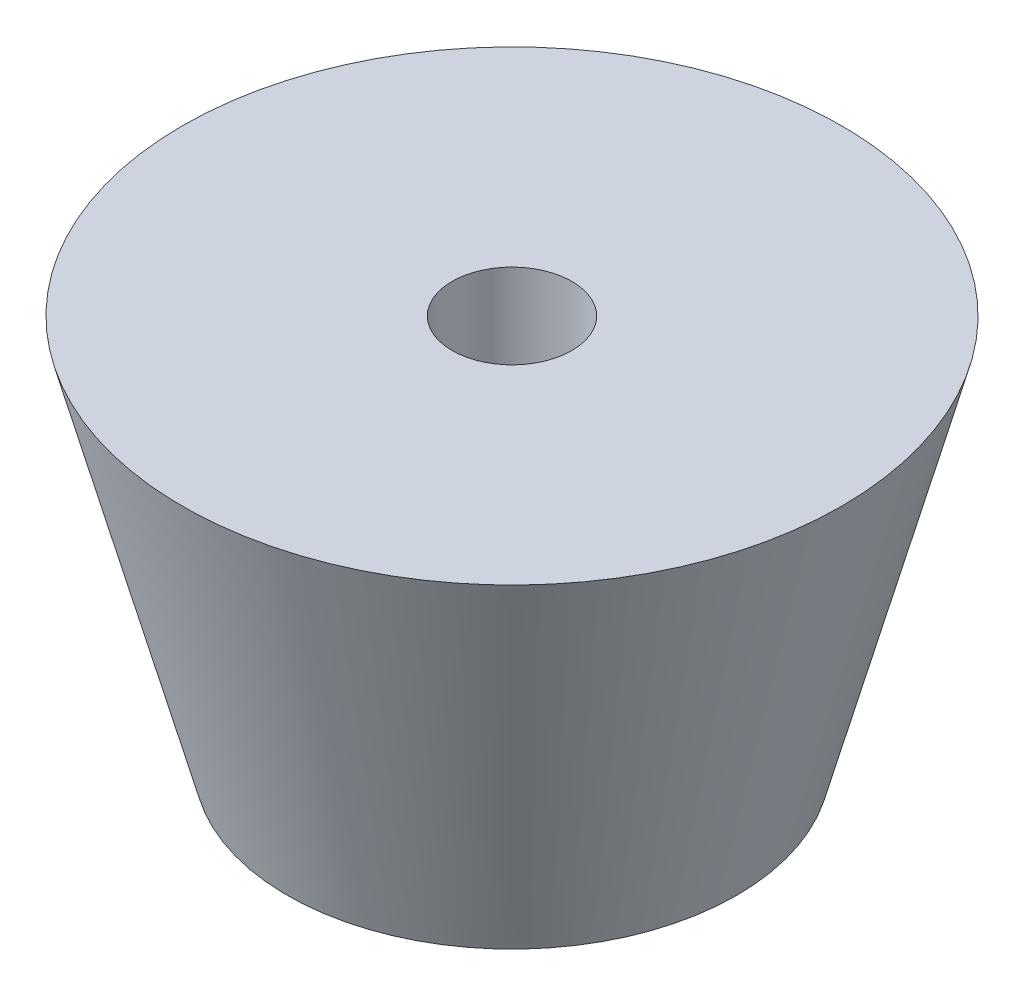
SolidWorks part; units mm, degrees
material "硅橡胶"
ref_plane "前视基准面" through (0, 0, 0) normal (0, 0, 1) x (1, 0, 0)
ref_plane "上视基准面" through (0, 0, 0) normal (0, 1, 0) x (1, 0, 0)
ref_plane "右视基准面" through (0, 0, 0) normal (1, 0, 0) x (0, 0, -1)
other "Configuration Table"
sketch "草图1" plane through (0, 0, 0) normal (0, 0, 1) x (1, 0, 0)
  line L0 (0, -1000) -> (0, 49000) construction
  line L1 (-11, 0) -> (-2, 0)
  line L2 (-2, 0) -> (-2, -6)
  line L3 (-2, -6) -> (-4, -6)
  line L4 (-4, -6) -> (-4, -13)
  line L5 (-4, -13) -> (-7.5, -13)
  line L6 (-7.5, -13) -> (-11, 0)
  point P5 (-2, -3)
  dimension "D1" = 11
  dimension "D2" = 2
  dimension "D3" = 4
  dimension "D4" = 7.5
  dimension "D5" = 13
  dimension "D6" = 6
other "对齐组1"
revolve "旋转1" add sketch "草图1" angle 360 about L0
